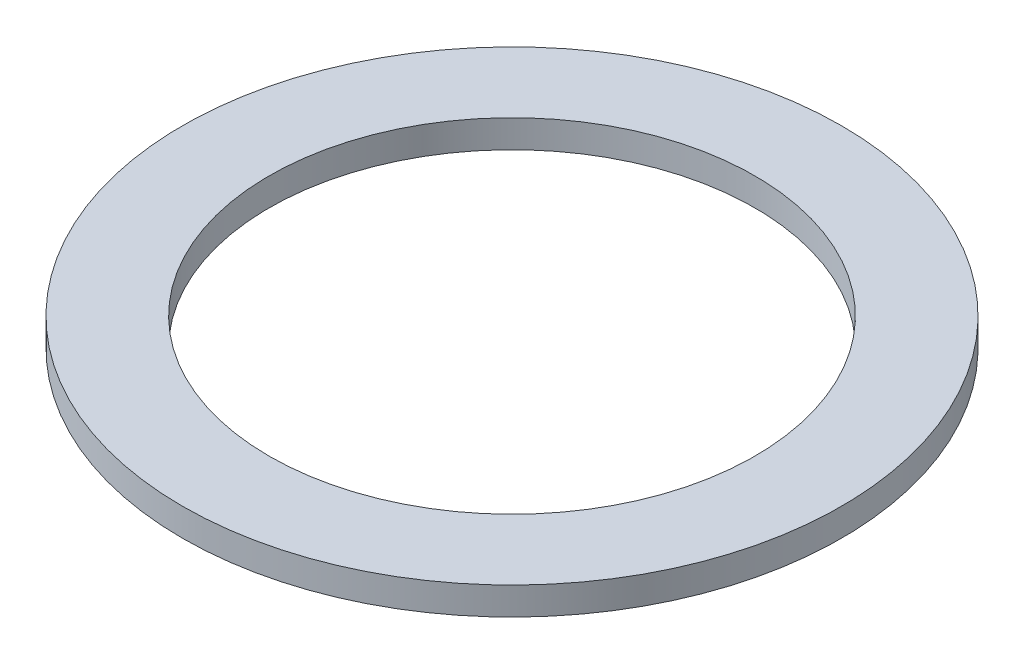
SolidWorks part; units mm, degrees
ref_plane "Front Plane" through (0, 0, 0) normal (0, 0, 1) x (1, 0, 0)
ref_plane "Top Plane" through (0, 0, 0) normal (0, 1, 0) x (1, 0, 0)
ref_plane "Right Plane" through (0, 0, 0) normal (1, 0, 0) x (0, 0, -1)
sketch "Sketch1" plane through (0, 0, 0) normal (0, 1, 0) x (1, 0, 0)
  circle A0 centre (0, 0) radius 35
  circle A1 centre (0, 0) radius 47.5
  dimension "D1" = 70
  dimension "D2" = 95
extrude "Boss-Extrude1" add sketch "Sketch1" along normal blind 4
